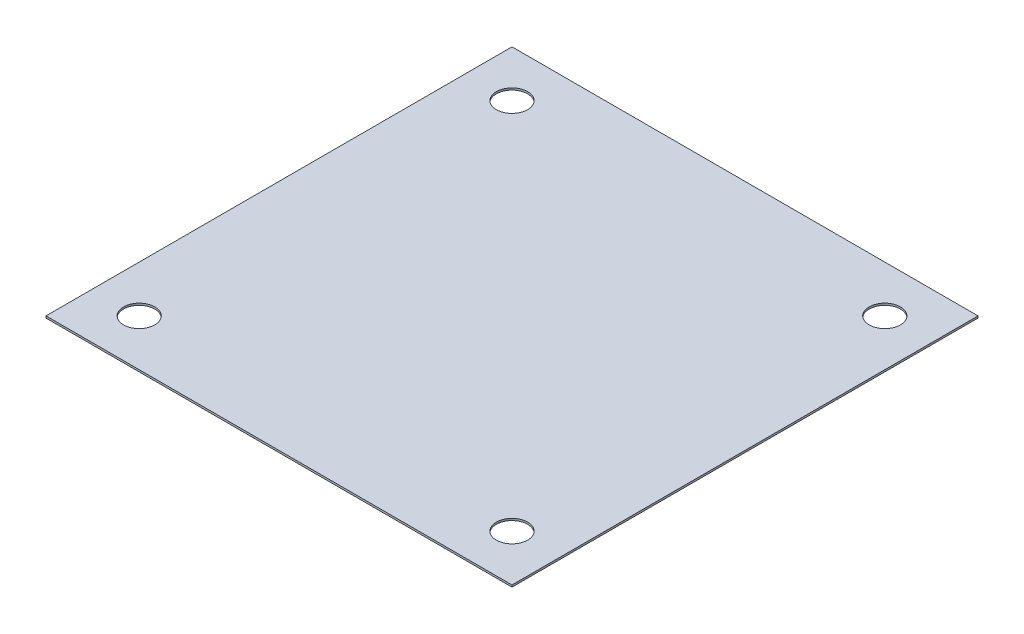
SolidWorks part; units mm, degrees
ref_plane "Front Plane" through (0, 0, 0) normal (0, 0, 1) x (1, 0, 0)
ref_plane "Top Plane" through (0, 0, 0) normal (0, 1, 0) x (1, 0, 0)
ref_plane "Right Plane" through (0, 0, 0) normal (1, 0, 0) x (0, 0, -1)
sketch "Sketch1" plane through (0, 0, 0) normal (0, 1, 0) x (1, 0, 0)
  line L0 (0, 762) -> (0, -762) construction
  line L1 (-762, 762) -> (762, 762)
  line L2 (-762, 762) -> (-762, -762)
  line L3 (-762, -762) -> (762, -762)
  line L4 (762, 762) -> (762, -762)
  dimension "D1" = 1524
extrude "Boss-Extrude1" add sketch "Sketch1" along normal blind 6.35
sketch "Sketch2" plane through (0, 6.35, 0) normal (0, 1, 0) x (1, 0, 0)
  circle A0 centre (609.6, 609.6) radius 51.1302
  circle A1 centre (609.6, -609.6) radius 51.1302
  circle A2 centre (-609.6, -609.6) radius 51.1302
  circle A3 centre (-609.6, 609.6) radius 51.1302
  circle A4 centre (609.6, -609.6) radius 51.1302 construction
  circle A5 centre (-609.6, -609.6) radius 51.1302 construction
  circle A6 centre (-609.6, 609.6) radius 51.1302 construction
  circle A7 centre (609.6, 609.6) radius 51.1302 construction
extrude "Cut-Extrude1" cut sketch "Sketch2" against normal up to next
